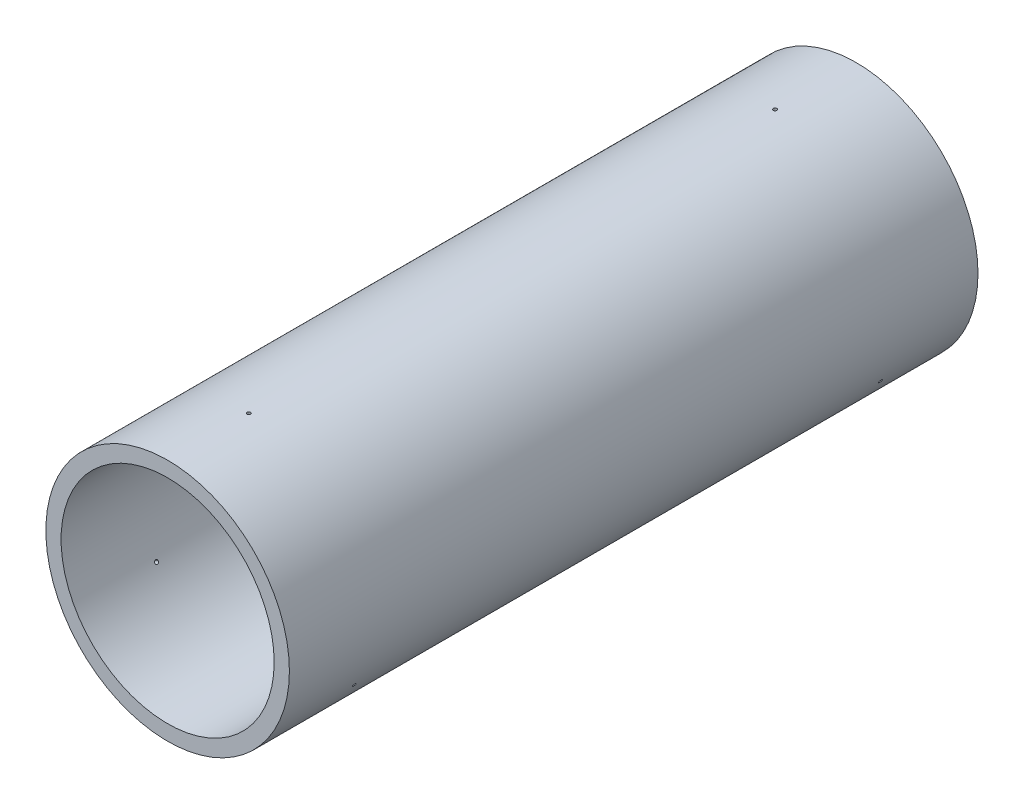
SolidWorks part; units mm, degrees
ref_plane "Front" through (0, 0, 0) normal (0, 0, 1) x (1, 0, 0)
ref_plane "Top" through (0, 0, 0) normal (0, 1, 0) x (1, 0, 0)
ref_plane "Right" through (0, 0, 0) normal (1, 0, 0) x (0, 0, -1)
sketch "Sketch1" plane through (0, 0, 0) normal (0, 0, 1) x (1, 0, 0)
  circle A0 centre (0, 0) radius 66.6496
  circle A1 centre (0, 0) radius 76.1746
  dimension "D1" = 152.3492
  dimension "D2" = 9.525
extrude "Boss-Extrude1" add sketch "Sketch1" along normal mid plane 430.7586
hole_wizard "#4-40 Tapped Hole1" positions "3DSketch2" profile "Sketch3" tap size "#4-40" standard "ANSI Inch"
sketch3d "3DSketch2"
  point P0 (0, 76.1746, 164.5793)
  dimension "D1" = 50.8
sketch "Sketch3" plane through (0, 76.1746, 164.5793) normal (1, 0, 0) x (0, 0, 1)
  line L0 (0, 0) -> (0, 152.3492)
  line L1 (0, 152.3492) -> (1.1303, 152.3492)
  line L2 (1.1303, 152.3492) -> (1.1303, 0)
  line L5 (1.1303, 0) -> (0, 0)
  line L11 (0, -6.35) -> (0, 107.95) construction
  dimension "Thru Tap Drill Dia." = 2.2606
  dimension "Thru Tap Drill Depth" = 152.3492
cosmetic thread "Hole Thread2" parameters "D2"=2.8448
pattern_circular "CirPattern1" count 3 over 360 about axis through (0, 0, 215.3793) along (0, 0, 1) of "#4-40 Tapped Hole1"
mirror "Mirror1" about plane through (0, 0, 0) normal (0, 0, 1) of "CirPattern1", "#4-40 Tapped Hole1"
chamfer "Chamfer1" [suppressed] distance 0.254 angle 45
